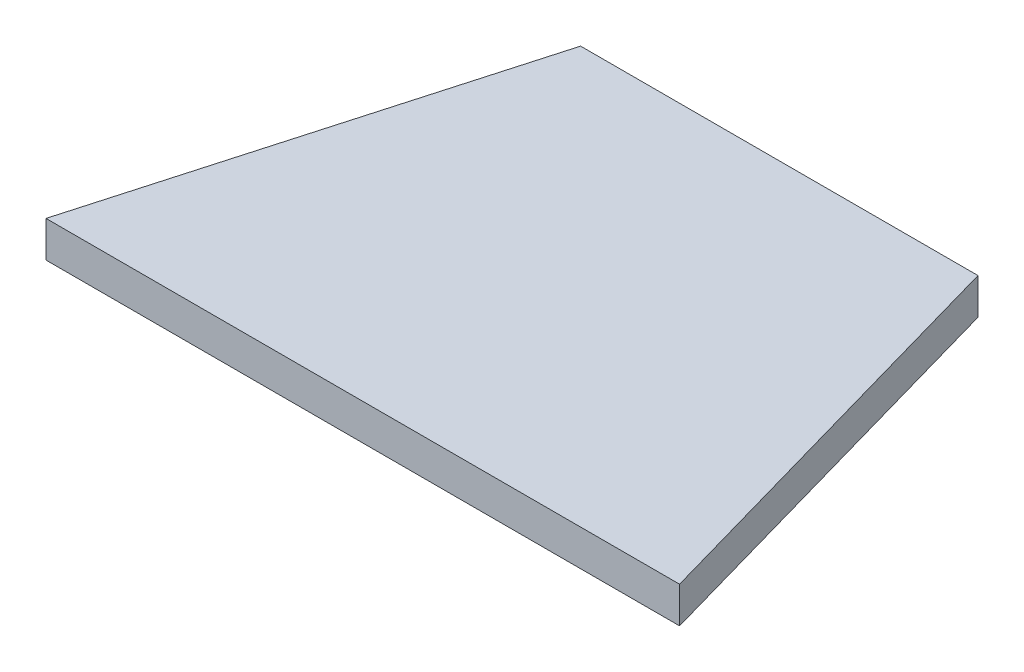
SolidWorks part; units mm, degrees
ref_plane "Front Plane" through (0, 0, 0) normal (0, 0, 1) x (1, 0, 0)
ref_plane "Top Plane" through (0, 0, 0) normal (0, 1, 0) x (1, 0, 0)
ref_plane "Right Plane" through (0, 0, 0) normal (1, 0, 0) x (0, 0, -1)
sketch "Sketch2" plane through (0, 0, 0) normal (0, 1, 0) x (1, 0, 0)
  line L0 (27.5119, 38.9524) -> (-27.5119, 38.9524)
  line L2 (-27.5119, 38.9524) -> (-43.8615, -18.718)
  line L3 (11.1622, -18.718) -> (-43.8615, -18.718)
  line L4 (11.1622, -18.718) -> (43.8615, -18.718)
  line L6 (43.8615, -18.718) -> (27.5119, 38.9524)
extrude "Boss-Extrude1" add sketch "Sketch2" along normal blind 5
